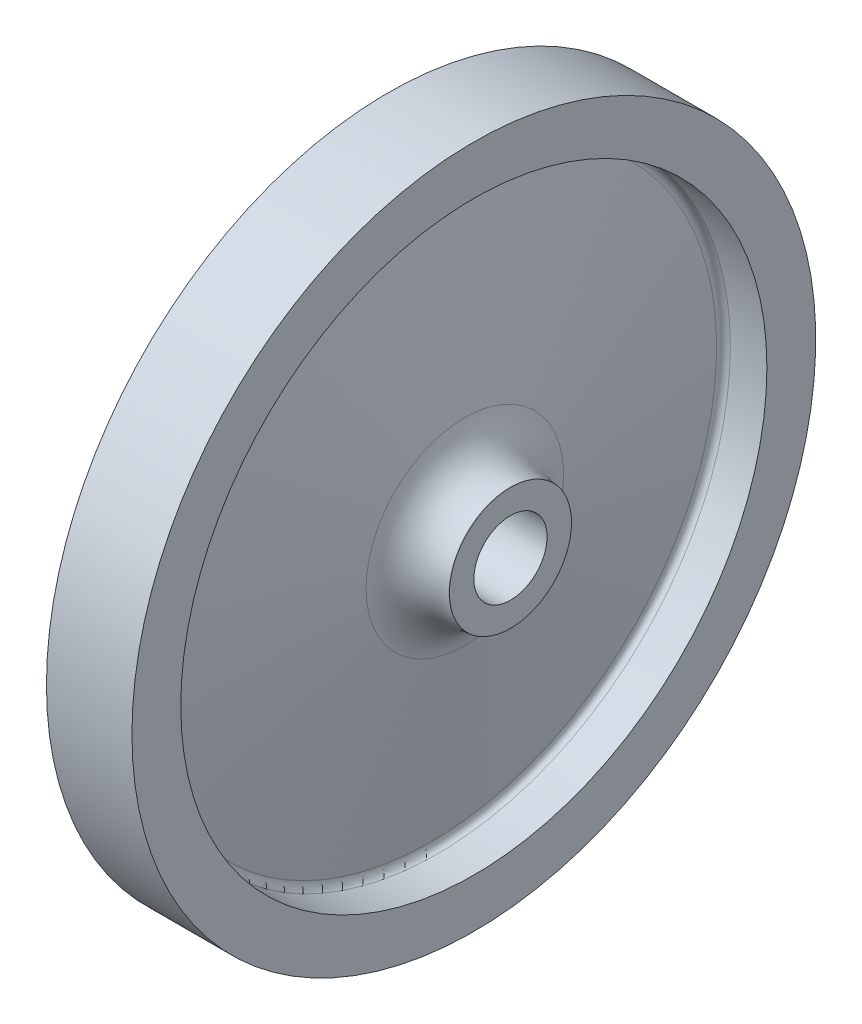
SolidWorks part; units mm, degrees
ref_plane "Front Plane" through (0, 0, 0) normal (0, 0, 1) x (1, 0, 0)
ref_plane "Top Plane" through (0, 0, 0) normal (0, 1, 0) x (1, 0, 0)
ref_plane "Right Plane" through (0, 0, 0) normal (1, 0, 0) x (0, 0, -1)
sketch "Sketch2" plane through (0, 0, 0) normal (0, 0, 1) x (1, 0, 0)
  line L0 (-25.0285, 0) -> (6.7215, 0) construction
  line L1 (-24.3191, 9.525) -> (7.4309, 9.525)
  line L2 (-24.3191, 15.875) -> (-14.1916, 15.875)
  line L3 (-24.3191, 76.2) -> (-23.4499, 76.2)
  line L4 (-24.3191, 88.9) -> (-2.0941, 88.9)
  line L5 (-24.3191, 88.9) -> (-24.3191, 76.2)
  line L6 (-2.0941, 88.9) -> (-2.0941, 76.2)
  line L7 (-24.3191, 9.525) -> (-24.3191, 15.875)
  line L8 (7.4309, 15.875) -> (7.4309, 9.525)
  line L9 (-21.8253, 74.8431) -> (-11.6922, 18.8675)
  line L10 (-4.4307, 25.6865) -> (-13.2228, 74.2549)
  line L11 (-11.5982, 76.2) -> (-2.0941, 76.2)
  line L12 (7.3164, 15.875) -> (7.4309, 15.875)
  arc A0 (-21.8253, 74.8431) -> (-23.4499, 76.2) centre (-23.4499, 74.549) ccw
  arc A1 (-13.2228, 74.2549) -> (-11.5982, 76.2) centre (-11.5982, 74.549) cw
  arc A2 (-4.4307, 25.6865) -> (7.3164, 15.875) centre (7.3164, 27.813) ccw
  arc A3 (-11.6922, 18.8675) -> (-14.1916, 15.875) centre (-14.1916, 18.415) cw
  point P19 (-13.5749, 76.2)
  point P22 (-2.6545, 15.875)
  point P25 (-21.8253, 74.8431)
  dimension "D7" = 1.651
  dimension "D8" = 1.651
  dimension "D9" = 11.938
  dimension "D10" = 2.54
  dimension "D1" = 19.05
  dimension "D2" = 31.75
  dimension "D3" = 31.75
  dimension "D4" = 31.75
  dimension "D5" = 177.8
  dimension "D6" = 12.7
  dimension "D11" = 22.225
revolve "Revolve1" add sketch "Sketch2" angle 360 about L0
